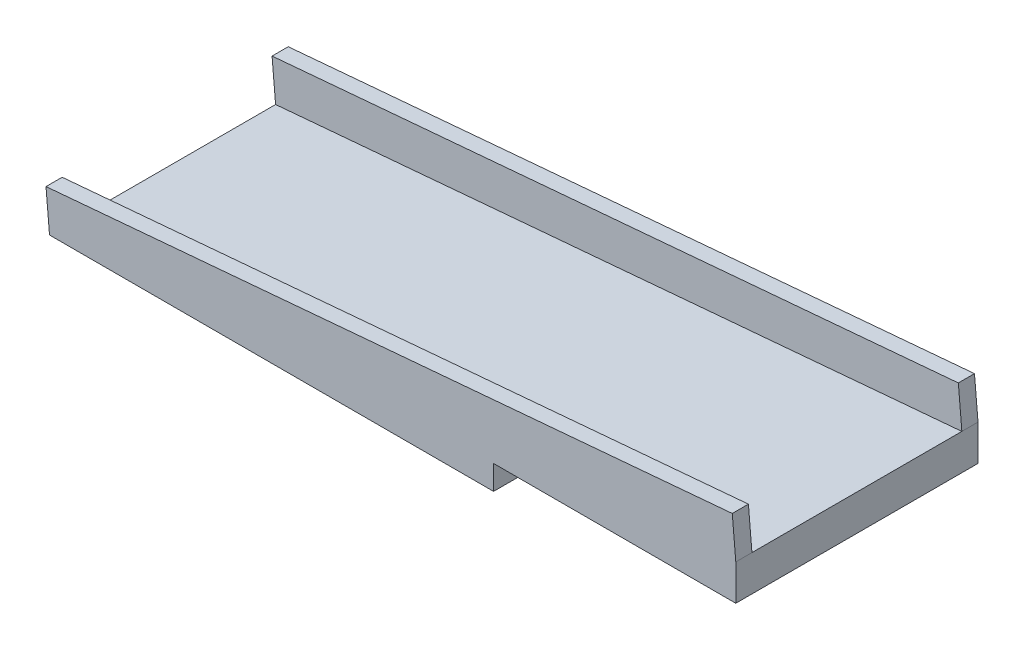
SolidWorks part; units mm, degrees
ref_plane "Front Plane" through (0, 0, 0) normal (0, 0, 1) x (1, 0, 0)
ref_plane "Top Plane" through (0, 0, 0) normal (0, 1, 0) x (1, 0, 0)
ref_plane "Right Plane" through (0, 0, 0) normal (1, 0, 0) x (0, 0, -1)
sketch "Sketch1" plane through (0, 0, 0) normal (0, 0, 1) x (1, 0, 0)
  line L0 (-43.3149, 0) -> (41.6851, 0)
  line L1 (41.6851, 0) -> (41.6851, 7.4365)
  line L2 (41.6851, 7.4365) -> (-43.3149, 0)
  line L4 (41.6851, 0) -> (11.6851, 0)
  line L5 (41.6851, 0) -> (41.6851, 3)
  line L6 (41.6851, 3) -> (11.6851, 3)
  line L7 (11.6851, 0) -> (11.6851, 3)
  dimension "D1" = 5
  dimension "D2" = 85
  dimension "D3" = 30
  dimension "D4" = 3
extrude "Boss-Extrude1" add sketch "Sketch1" along normal blind 30 contours L0 L7 L6 L1 L2
sketch "Sketch2" plane through (-0.329, 3.7608, 0) normal (-0.0872, 0.9962, 0) x (0.9962, 0.0872, 0)
  line L0 (42.1746, -30) -> (42.1746, 0) construction
  line L1 (-43.1501, -30) -> (42.1746, -30)
  line L2 (-43.1501, -30) -> (-43.1501, -28)
  line L3 (-43.1501, -28) -> (42.1746, -28)
  line L4 (42.1746, -30) -> (42.1746, -28)
  line L6 (-43.1501, 0) -> (42.1746, 0)
  line L7 (-43.1501, 0) -> (-43.1501, -2)
  line L8 (-43.1501, -2) -> (42.1746, -2)
  line L9 (42.1746, 0) -> (42.1746, -2)
  dimension "D1" = 2
  dimension "D2" = 2
extrude "Boss-Extrude2" add sketch "Sketch2" along normal blind 5
